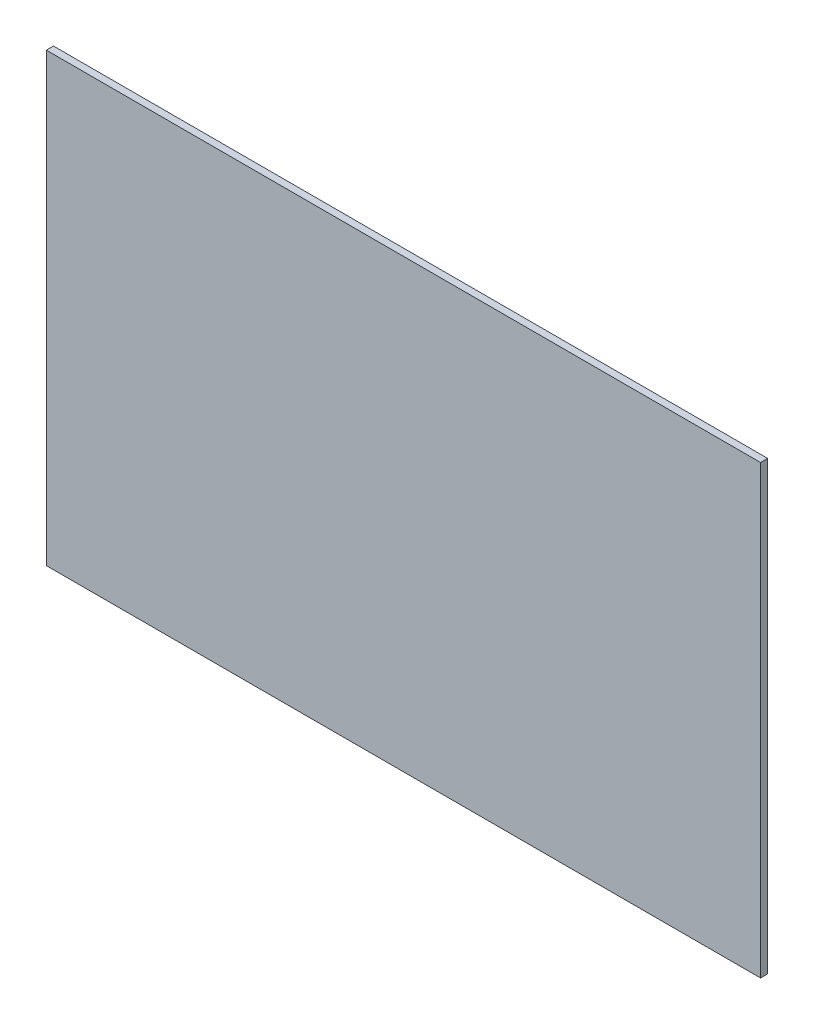
SolidWorks part; units mm, degrees
material "Corrugated Paper"
ref_plane "Front Plane" through (0, 0, 0) normal (0, 0, 1) x (1, 0, 0)
ref_plane "Top Plane" through (0, 0, 0) normal (0, 1, 0) x (1, 0, 0)
ref_plane "Right Plane" through (0, 0, 0) normal (1, 0, 0) x (0, 0, -1)
sketch "Sketch1" plane through (0, 0, 0) normal (0, 0, 1) x (1, 0, 0)
  line L1 (0, 0) -> (50.8, 0)
  line L2 (0, 0) -> (0, 31.75)
  line L3 (0, 31.75) -> (50.8, 31.75)
  line L4 (50.8, 0) -> (50.8, 31.75)
  dimension "D1" = 50.8
  dimension "D2" = 31.75
extrude "Boss-Extrude1" add sketch "Sketch1" along normal blind 0.508
